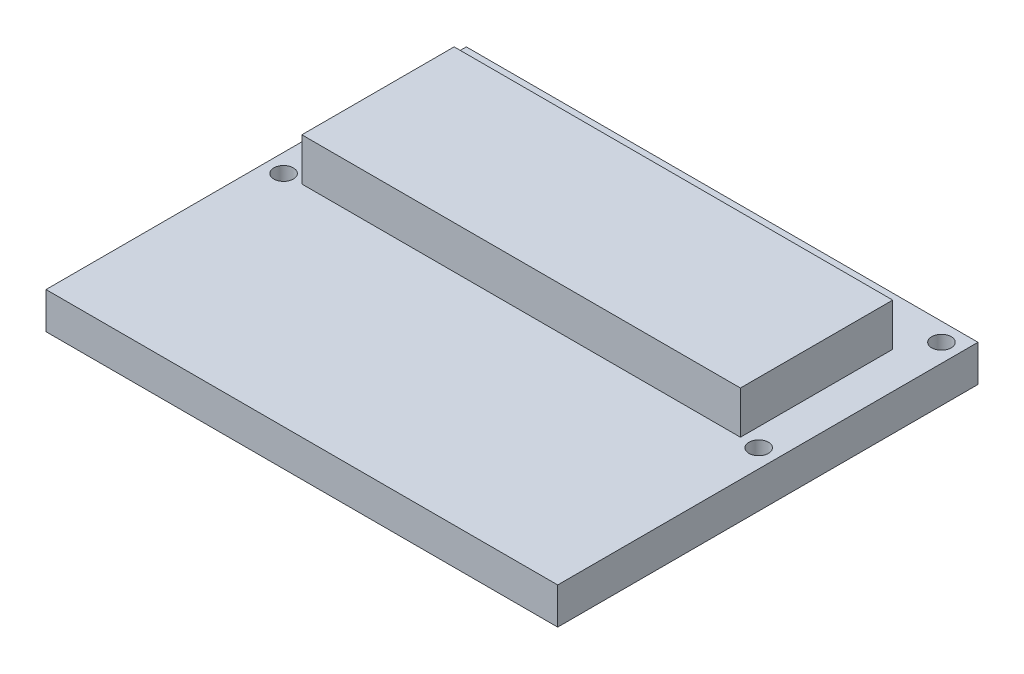
SolidWorks part; units mm, degrees
ref_plane "Front Plane" through (0, 0, 0) normal (0, 0, 1) x (1, 0, 0)
ref_plane "Top Plane" through (0, 0, 0) normal (0, 1, 0) x (1, 0, 0)
ref_plane "Right Plane" through (0, 0, 0) normal (1, 0, 0) x (0, 0, -1)
sketch "Sketch1" plane through (0, 0, 0) normal (0, 1, 0) x (1, 0, 0)
  line L1 (42, 34.5) -> (-42, 34.5)
  line L2 (42, 34.5) -> (42, -34.5)
  line L3 (42, -34.5) -> (-42, -34.5)
  line L4 (-42, 34.5) -> (-42, -34.5)
  line L5 (42, 34.5) -> (-42, -34.5) construction
  line L6 (42, -34.5) -> (-42, 34.5) construction
  point P0 (0, 0)
extrude "Boss-Extrude1" add sketch "Sketch1" along normal blind 6
sketch "Sketch2" plane through (0, 6, 0) normal (0, 1, 0) x (1, 0, 0)
  line L1 (36, 26.5) -> (-36, 26.5)
  line L2 (36, 26.5) -> (36, 1.5)
  line L3 (36, 1.5) -> (-36, 1.5)
  line L4 (-36, 26.5) -> (-36, 1.5)
  line L5 (36, 26.5) -> (-36, 1.5) construction
  line L6 (36, 1.5) -> (-36, 26.5) construction
  point P0 (0, 14)
extrude "Boss-Extrude2" add sketch "Sketch2" along normal blind 7
sketch "Sketch3" plane through (0, 6, 0) normal (0, 1, 0) x (1, 0, 0)
  circle A0 centre (-39, 31.5) radius 1.6
extrude "Cut-Extrude1" cut sketch "Sketch3" against normal through all
sketch "Sketch4" plane through (0, 6, 0) normal (0, 1, 0) x (1, 0, 0)
  circle A0 centre (39, 31.5) radius 1.6
extrude "Cut-Extrude2" cut sketch "Sketch4" against normal through all
sketch "Sketch5" plane through (0, 6, 0) normal (0, 1, 0) x (1, 0, 0)
  circle A0 centre (-39, 1.5) radius 1.6
extrude "Cut-Extrude3" cut sketch "Sketch5" against normal through all
sketch "Sketch6" plane through (0, 6, 0) normal (0, 1, 0) x (1, 0, 0)
  circle A0 centre (39, 1.5) radius 1.6
extrude "Cut-Extrude4" cut sketch "Sketch6" against normal through all
